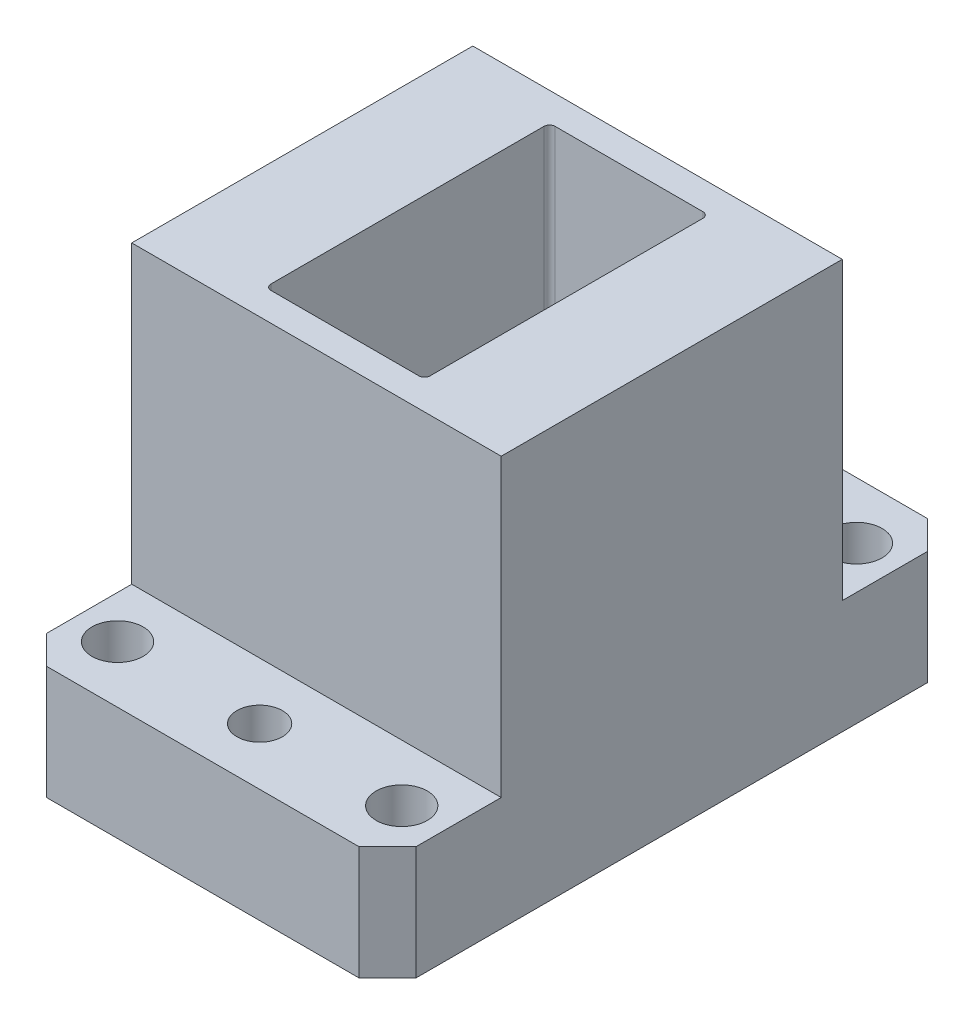
SolidWorks part; units mm, degrees
ref_plane "前基準面" through (0, 0, 0) normal (0, 0, 1) x (1, 0, 0)
ref_plane "上基準面" through (0, 0, 0) normal (0, 1, 0) x (1, 0, 0)
ref_plane "右基準面" through (0, 0, 0) normal (1, 0, 0) x (0, 0, -1)
sketch "草圖1" plane through (0, 0, 0) normal (0, 0, 1) x (1, 0, 0)
  line L0 (-32.5, -36) -> (32.5, 36) construction
  line L1 (-32.5, 36) -> (32.5, 36)
  line L2 (-32.5, 36) -> (-32.5, -36)
  line L3 (-32.5, -36) -> (32.5, -36)
  line L4 (32.5, 36) -> (32.5, -36)
  dimension "D1" = 65
  dimension "D2" = 72
extrude "伸長1" add sketch "草圖1" along normal mid plane 100
sketch "草圖2" plane through (0, 36, 0) normal (0, 1, 0) x (1, 0, 0)
  line L1 (0, 0) -> (18.8209, 0) construction
  line L2 (-14, 25) -> (14, 25)
  line L3 (-14, 25) -> (-14, -25)
  line L4 (-14, -25) -> (14, -25)
  line L5 (0, 0) -> (0, -31.638) construction
  line L7 (14, 25) -> (14, -25)
  dimension "D1" = 28
  dimension "D2" = 50
extrude "除料-伸長1" cut sketch "草圖2" against normal through all
sketch "草圖4" plane through (0, 36, 0) normal (0, 1, 0) x (1, 0, 0)
  line L0 (32.5, -50) -> (32.5, 50) construction
  line L1 (-32.5, -50) -> (32.5, -50)
  line L2 (32.5, 50) -> (-32.5, 50) construction
  line L3 (-32.5, 30) -> (-32.5, 50)
  line L4 (32.5, 30) -> (32.5, 50)
  line L5 (32.5, 50) -> (-32.5, 50)
  line L6 (-32.5, -50) -> (-32.5, -30)
  line L7 (-32.5, -50) -> (-32.5, 50) construction
  line L8 (-32.5, 30) -> (32.5, 30)
  line L9 (32.5, -50) -> (32.5, 50) construction
  line L10 (-32.5, -30) -> (32.5, -30)
  line L12 (32.5, -50) -> (32.5, -30)
  line L13 (-14, 0) -> (9.5677, 0) construction
  line L14 (-14, 25) -> (-14, -25) construction
  dimension "D1" = 60
extrude "除料-伸長3" cut sketch "草圖4" against normal blind 52
chamfer "導角1" distance 5 angle 45 4 edges at (-32.5, -26, 50) (32.5, -26, 50) (-32.5, -26, -50) (32.5, -26, -50)
hole_wizard "Ø9.0 (9) 直徑孔1" positions "草圖6" profile "草圖7" hole size "Ø9.0" standard "ISO" end condition up to next
sketch "草圖6" plane through (0, -16, 0) normal (0, 1, 0) x (-1, 0, 0)
  line L0 (0, 0) -> (0, 10.8264) construction
  line L3 (-27.5, -50) -> (27.5, -50) construction
  line L4 (27.5, 50) -> (-27.5, 50) construction
  point P0 (25, -40)
  point P1 (-25, -40)
  point P11 (-25, 40)
  point P13 (25, 40)
  dimension "D1" = 10
  dimension "D2" = 50
  dimension "D3" = 10
sketch "草圖7" plane through (-25, -16, -40) normal (1, 0, 0) x (0, 0, 1)
  line L0 (0, 0) -> (0, 20)
  line L1 (0, 20) -> (4.5, 20)
  line L2 (4.5, 20) -> (4.5, 0)
  line L5 (4.5, 0) -> (0, 0)
  line L11 (0, -6.35) -> (0, 107.95) construction
  dimension "貫穿孔直徑" = 9
  dimension "貫穿孔深度" = 20
hole_wizard "Ø8.0 (8) 直徑孔1" positions "草圖9" profile "草圖8" hole size "Ø8.0" standard "GB" end condition through all
sketch "草圖9" plane through (0, -16, 0) normal (0, 1, 0) x (-1, 0, 0)
  line L4 (-27.5, -50) -> (27.5, -50) construction
  line L5 (27.5, 50) -> (-27.5, 50) construction
  point P0 (0, -40)
  point P1 (0, 40)
  dimension "D1" = 10
  dimension "D2" = 10
sketch "草圖8" plane through (0, -16, -40) normal (1, 0, 0) x (0, 0, 1)
  line L0 (0, 0) -> (0, 20)
  line L1 (0, 20) -> (4, 20)
  line L2 (4, 20) -> (4, 0)
  line L5 (4, 0) -> (0, 0)
  line L11 (0, -6.35) -> (0, 107.95) construction
  dimension "貫穿孔直徑" = 8
  dimension "貫穿孔深度" = 20
fillet "圓角1" radius 1 4 edges at (14, 0, -25) (14, 0, 25) (-14, 0, -25) (-14, 0, 25)
